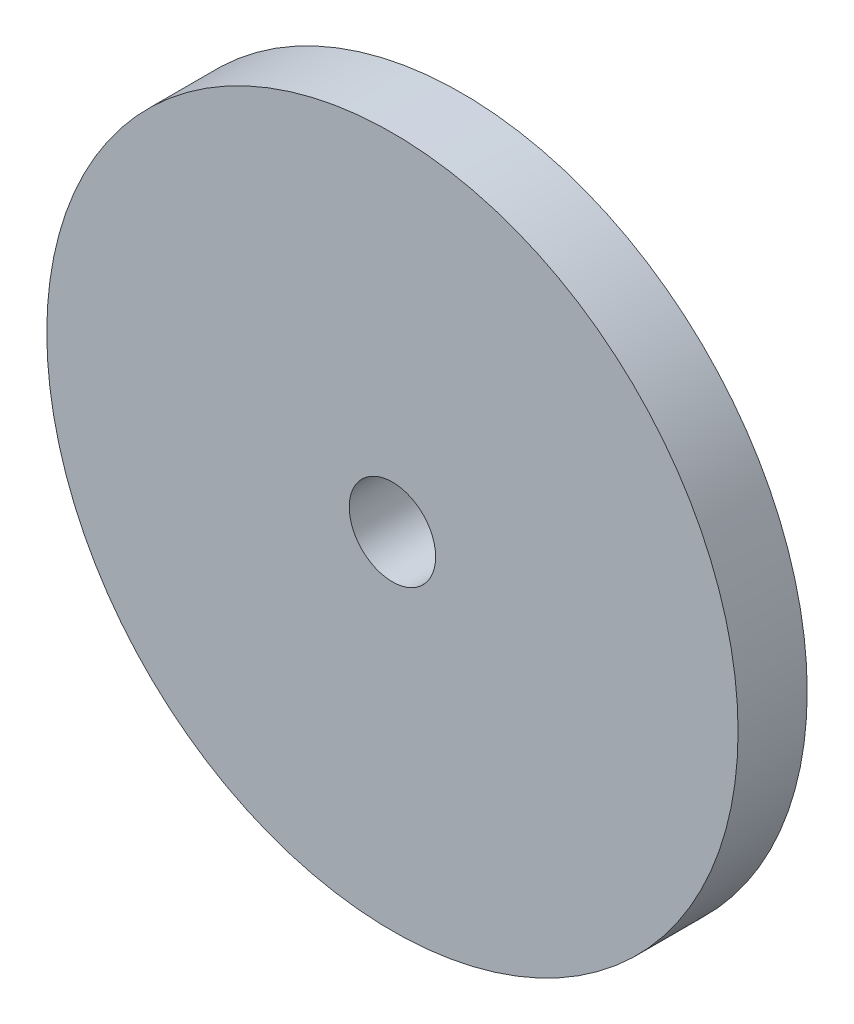
SolidWorks part; units mm, degrees
ref_plane "Plano frontal" through (0, 0, 0) normal (0, 0, 1) x (1, 0, 0)
ref_plane "Plano superior" through (0, 0, 0) normal (0, 1, 0) x (1, 0, 0)
ref_plane "Plano direito" through (0, 0, 0) normal (1, 0, 0) x (0, 0, -1)
sketch "Esboço1" plane through (0, 0, 0) normal (0, 0, 1) x (1, 0, 0)
  circle A0 centre (0, 0) radius 20
  circle A1 centre (0, 0) radius 2.5
  dimension "D1" = 40
  dimension "D2" = 5
extrude "Ressalto-extrusão1" add sketch "Esboço1" along normal blind 4
